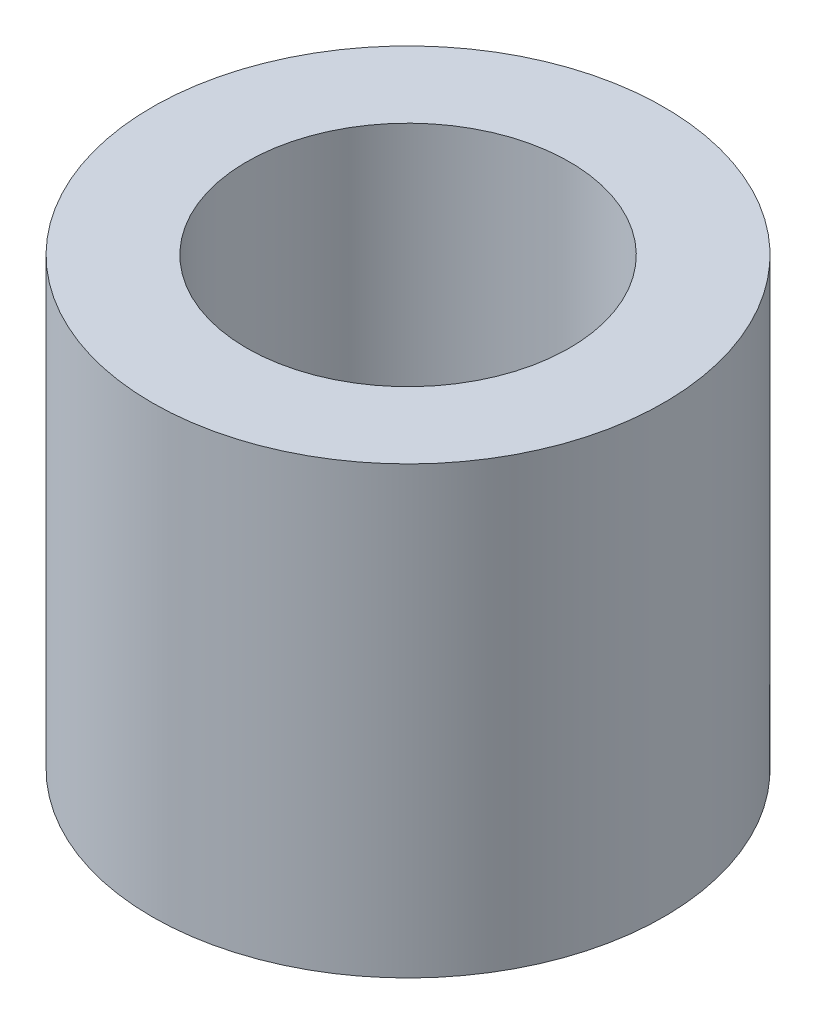
SolidWorks part; units mm, degrees
ref_plane "前视基准面" through (0, 0, 0) normal (0, 0, 1) x (1, 0, 0)
ref_plane "上视基准面" through (0, 0, 0) normal (0, 1, 0) x (1, 0, 0)
ref_plane "右视基准面" through (0, 0, 0) normal (1, 0, 0) x (0, 0, -1)
sketch "草图1" plane through (0, 0, 0) normal (0, 1, 0) x (1, 0, 0)
  circle A0 centre (0, 0) radius 145
  circle A1 centre (0, 0) radius 230
  dimension "D1" = 290
  dimension "D2" = 460
extrude "凸台-拉伸1" add sketch "草图1" along normal blind 400
sketch "草图2" plane through (0, 400, 0) normal (0, 1, 0) x (1, 0, 0)
  line L0 (0, 0) -> (-230, 0) construction
  line L4 (0, 0) -> (-212.4923, 88.0172) construction
  line L5 (-214.3754, 83.3257) -> (-212.0657, 82.369)
  line L6 (-212.0657, 82.369) -> (-208.1968, 91.7094)
  line L7 (-208.1968, 91.7094) -> (-210.5065, 92.6661)
  line L8 (-157.2531, 164.4019) -> (-159.0209, 166.1697)
  line L9 (-164.4019, 157.2531) -> (-157.2531, 164.4019)
  line L10 (-166.1697, 159.0209) -> (-164.4019, 157.2531)
  line L11 (-82.369, 212.0657) -> (-83.3257, 214.3754)
  line L12 (-91.7094, 208.1968) -> (-82.369, 212.0657)
  line L13 (-92.6661, 210.5065) -> (-91.7094, 208.1968)
  line L14 (5.055, 227.4444) -> (5.055, 229.9444)
  line L15 (-5.055, 227.4444) -> (5.055, 227.4444)
  line L16 (-5.055, 229.9444) -> (-5.055, 227.4444)
  line L17 (91.7094, 208.1968) -> (92.6661, 210.5065)
  line L18 (82.369, 212.0657) -> (91.7094, 208.1968)
  line L19 (83.3257, 214.3754) -> (82.369, 212.0657)
  line L20 (164.4019, 157.2531) -> (166.1697, 159.0209)
  line L21 (157.2531, 164.4019) -> (164.4019, 157.2531)
  line L22 (159.0209, 166.1697) -> (157.2531, 164.4019)
  line L23 (212.0657, 82.369) -> (214.3754, 83.3257)
  line L24 (208.1968, 91.7094) -> (212.0657, 82.369)
  line L25 (210.5065, 92.6661) -> (208.1968, 91.7094)
  line L26 (227.4444, -5.055) -> (229.9444, -5.055)
  line L27 (227.4444, 5.055) -> (227.4444, -5.055)
  line L28 (229.9444, 5.055) -> (227.4444, 5.055)
  line L29 (208.1968, -91.7094) -> (210.5065, -92.6661)
  line L30 (212.0657, -82.369) -> (208.1968, -91.7094)
  line L31 (214.3754, -83.3257) -> (212.0657, -82.369)
  line L32 (157.2531, -164.4019) -> (159.0209, -166.1697)
  line L33 (164.4019, -157.2531) -> (157.2531, -164.4019)
  line L34 (166.1697, -159.0209) -> (164.4019, -157.2531)
  line L35 (82.369, -212.0657) -> (83.3257, -214.3754)
  line L36 (91.7094, -208.1968) -> (82.369, -212.0657)
  line L37 (92.6661, -210.5065) -> (91.7094, -208.1968)
  line L38 (-5.055, -227.4444) -> (-5.055, -229.9444)
  line L39 (5.055, -227.4444) -> (-5.055, -227.4444)
  line L40 (5.055, -229.9444) -> (5.055, -227.4444)
  line L41 (-91.7094, -208.1968) -> (-92.6661, -210.5065)
  line L42 (-82.369, -212.0657) -> (-91.7094, -208.1968)
  line L43 (-83.3257, -214.3754) -> (-82.369, -212.0657)
  line L44 (-164.4019, -157.2531) -> (-166.1697, -159.0209)
  line L45 (-157.2531, -164.4019) -> (-164.4019, -157.2531)
  line L46 (-159.0209, -166.1697) -> (-157.2531, -164.4019)
  line L47 (-212.0657, -82.369) -> (-214.3754, -83.3257)
  line L48 (-208.1968, -91.7094) -> (-212.0657, -82.369)
  line L49 (-210.5065, -92.6661) -> (-208.1968, -91.7094)
  line L50 (-227.4444, 5.055) -> (-229.9444, 5.055)
  line L51 (-227.4444, -5.055) -> (-227.4444, 5.055)
  line L52 (-229.9444, -5.055) -> (-227.4444, -5.055)
  line L53 (-160.8275, 160.8275) -> (0, 0) construction
  line L54 (0, 227.4444) -> (0, 0) construction
  circle A2 centre (0, 0) radius 230 construction
  arc A3 (-210.5065, 92.6661) -> (-214.3754, 83.3257) centre (0, 0) ccw
  arc A4 (-159.0209, 166.1697) -> (-166.1697, 159.0209) centre (0, 0) ccw
  arc A5 (-83.3257, 214.3754) -> (-92.6661, 210.5065) centre (0, 0) ccw
  arc A6 (5.055, 229.9444) -> (-5.055, 229.9444) centre (0, 0) ccw
  arc A7 (92.6661, 210.5065) -> (83.3257, 214.3754) centre (0, 0) ccw
  arc A8 (166.1697, 159.0209) -> (159.0209, 166.1697) centre (0, 0) ccw
  arc A9 (214.3754, 83.3257) -> (210.5065, 92.6661) centre (0, 0) ccw
  arc A10 (229.9444, -5.055) -> (229.9444, 5.055) centre (0, 0) ccw
  arc A11 (210.5065, -92.6661) -> (214.3754, -83.3257) centre (0, 0) ccw
  arc A12 (159.0209, -166.1697) -> (166.1697, -159.0209) centre (0, 0) ccw
  arc A13 (83.3257, -214.3754) -> (92.6661, -210.5065) centre (0, 0) ccw
  arc A14 (-5.055, -229.9444) -> (5.055, -229.9444) centre (0, 0) ccw
  arc A15 (-92.6661, -210.5065) -> (-83.3257, -214.3754) centre (0, 0) ccw
  arc A16 (-166.1697, -159.0209) -> (-159.0209, -166.1697) centre (0, 0) ccw
  arc A17 (-214.3754, -83.3257) -> (-210.5065, -92.6661) centre (0, 0) ccw
  arc A18 (-229.9444, 5.055) -> (-229.9444, -5.055) centre (0, 0) ccw
  dimension "D1" = 10.11
  dimension "D2" = 2.5
  dimension "D4" = 16
extrude "切除-拉伸1" [suppressed] cut sketch "草图2" against normal up to next
